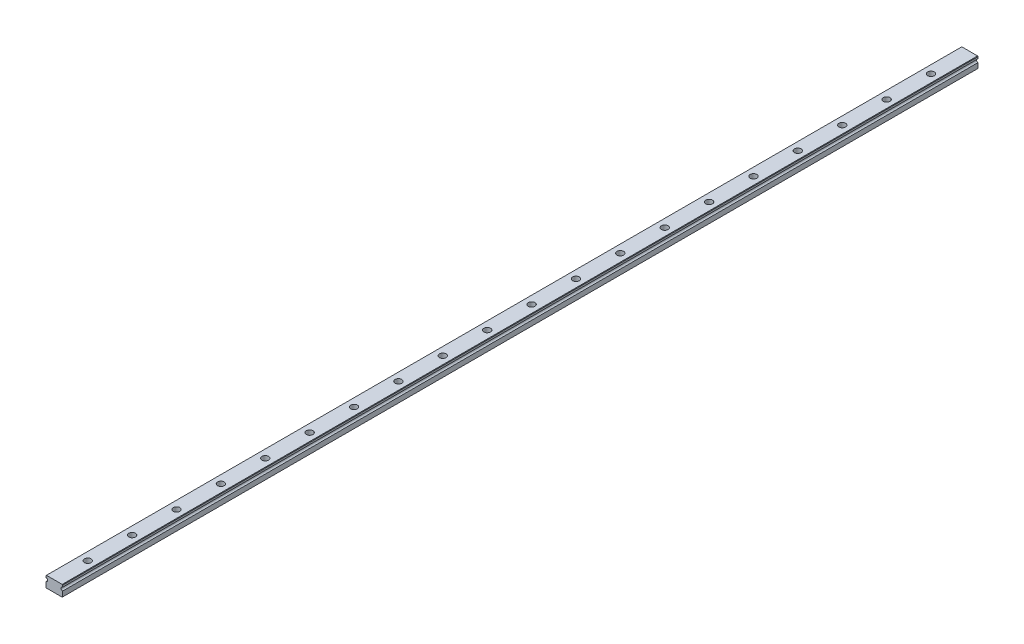
SolidWorks part; units mm, degrees
material "镀铬不锈钢"
ref_plane "前视基准面" through (0, 0, 0) normal (0, 0, 1) x (1, 0, 0)
ref_plane "上视基准面" through (0, 0, 0) normal (0, 1, 0) x (1, 0, 0)
ref_plane "右视基准面" through (0, 0, 0) normal (1, 0, 0) x (0, 0, -1)
other "Configuration Table"
sketch "草图1" plane through (0, 0, 0) normal (0, 0, 1) x (1, 0, 0)
  line L0 (-7.6432, 0.2342) -> (-7.6432, -4.3658)
  line L1 (-7.6432, -4.3658) -> (-7.2432, -4.7658)
  line L2 (-7.2432, -4.7658) -> (6.9568, -4.7658)
  line L3 (6.9568, -4.7658) -> (7.3568, -4.3658)
  line L4 (7.3568, -4.3658) -> (7.3568, 0.2342)
  line L5 (7.3568, 3.2342) -> (7.3568, 4.8342)
  line L6 (7.3568, 4.8342) -> (6.9568, 5.2342)
  line L7 (6.9568, 5.2342) -> (-7.2432, 5.2342)
  line L8 (-7.2432, 5.2342) -> (-7.6432, 4.8342)
  line L9 (-7.6432, 4.8342) -> (-7.6432, 3.2342)
  arc A0 (5.8568, 1.7342) -> (7.3568, 0.2342) centre (7.3568, 1.7342) ccw
  arc A1 (7.3568, 3.2342) -> (5.8568, 1.7342) centre (7.3568, 1.7342) ccw
  arc A2 (-7.6432, 0.2342) -> (-7.6432, 3.2342) centre (-7.6432, 1.7342) ccw
extrude "凸台-拉伸1" add sketch "草图1" along normal blind 1000
sketch "草图2" plane through (0, 5.2342, 0) normal (0, 1, 0) x (1, 0, 0)
  line L0 (6.9568, 0) -> (-7.2432, 0) construction
  circle A0 centre (0, -20) radius 1.5
  dimension "D1" = 3
  dimension "D2" = 20
extrude "切除-拉伸1" cut sketch "草图2" against normal blind 20
sketch "草图3" plane through (0, 5.2342, 0) normal (0, 1, 0) x (1, 0, 0)
  circle A0 centre (0, -20) radius 3
  dimension "D1" = 6
extrude "切除-拉伸2" cut sketch "草图3" against normal blind 4.5
sketch "草图4" plane through (0, 5.2342, 0) normal (0, 1, 0) x (1, 0, 0)
  line L0 (0, 0) -> (0, -1341.5051) construction
pattern_linear "阵列(线性)1" count 25 spacing 40 along (0, 0, 1) of "切除-拉伸2", "切除-拉伸1"
sketch "草图5" plane through (0, 0, 1000) normal (0, 0, 1) x (1, 0, 0)
  line L10 (-7.6432, 0.2342) -> (-7.6432, -4.3658)
  line L11 (-7.6432, -4.3658) -> (-7.2432, -4.7658)
  line L12 (-7.2432, -4.7658) -> (6.9568, -4.7658)
  line L13 (6.9568, -4.7658) -> (7.3568, -4.3658)
  line L14 (7.3568, -4.3658) -> (7.3568, 0.2342)
  line L15 (7.3568, 3.2342) -> (7.3568, 4.8342)
  line L16 (7.3568, 4.8342) -> (6.9568, 5.2342)
  line L17 (6.9568, 5.2342) -> (-7.2432, 5.2342)
  line L18 (-7.2432, 5.2342) -> (-7.6432, 4.8342)
  line L19 (-7.6432, 4.8342) -> (-7.6432, 3.2342)
  line L20 (-7.6432, 0.2342) -> (-7.6432, -4.3658)
  line L21 (-7.6432, -4.3658) -> (-7.2432, -4.7658)
  line L22 (-7.2432, -4.7658) -> (6.9568, -4.7658)
  line L23 (6.9568, -4.7658) -> (7.3568, -4.3658)
  line L24 (7.3568, -4.3658) -> (7.3568, 0.2342)
  line L25 (7.3568, 3.2342) -> (7.3568, 4.8342)
  line L26 (7.3568, 4.8342) -> (6.9568, 5.2342)
  line L27 (6.9568, 5.2342) -> (-7.2432, 5.2342)
  line L28 (-7.2432, 5.2342) -> (-7.6432, 4.8342)
  line L29 (-7.6432, 4.8342) -> (-7.6432, 3.2342)
  arc A2 (-7.6432, 0.2342) -> (-7.6432, 3.2342) centre (-7.6432, 1.7342) ccw
  arc A3 (7.3568, 3.2342) -> (7.3568, 0.2342) centre (7.3568, 1.7342) ccw
  arc A4 (-7.6432, 0.2342) -> (-7.6432, 3.2342) centre (-7.6432, 1.7342) ccw
  arc A5 (7.3568, 3.2342) -> (7.3568, 0.2342) centre (7.3568, 1.7342) ccw
  dimension "D1" = 0
sketch "草图6" plane through (0, 0, 0) normal (0, 0, -1) x (-1, 0, 0)
  line L10 (7.6432, 3.2342) -> (7.6432, 4.8342)
  line L11 (7.6432, 4.8342) -> (7.2432, 5.2342)
  line L12 (7.2432, 5.2342) -> (-6.9568, 5.2342)
  line L13 (-6.9568, 5.2342) -> (-7.3568, 4.8342)
  line L14 (-7.3568, 4.8342) -> (-7.3568, 3.2342)
  line L15 (-7.3568, 0.2342) -> (-7.3568, -4.3658)
  line L16 (-7.3568, -4.3658) -> (-6.9568, -4.7658)
  line L17 (-6.9568, -4.7658) -> (7.2432, -4.7658)
  line L18 (7.2432, -4.7658) -> (7.6432, -4.3658)
  line L19 (7.6432, -4.3658) -> (7.6432, 0.2342)
  line L20 (7.6432, 3.2342) -> (7.6432, 4.8342)
  line L21 (7.6432, 4.8342) -> (7.2432, 5.2342)
  line L22 (7.2432, 5.2342) -> (-6.9568, 5.2342)
  line L23 (-6.9568, 5.2342) -> (-7.3568, 4.8342)
  line L24 (-7.3568, 4.8342) -> (-7.3568, 3.2342)
  line L25 (-7.3568, 0.2342) -> (-7.3568, -4.3658)
  line L26 (-7.3568, -4.3658) -> (-6.9568, -4.7658)
  line L27 (-6.9568, -4.7658) -> (7.2432, -4.7658)
  line L28 (7.2432, -4.7658) -> (7.6432, -4.3658)
  line L29 (7.6432, -4.3658) -> (7.6432, 0.2342)
  arc A2 (7.6432, 3.2342) -> (7.6432, 0.2342) centre (7.6432, 1.7342) ccw
  arc A3 (-7.3568, 0.2342) -> (-7.3568, 3.2342) centre (-7.3568, 1.7342) ccw
  arc A4 (7.6432, 3.2342) -> (7.6432, 0.2342) centre (7.6432, 1.7342) ccw
  arc A5 (-7.3568, 0.2342) -> (-7.3568, 3.2342) centre (-7.3568, 1.7342) ccw
  dimension "D1" = 0
extrude "切除-拉伸4" cut sketch "草图6" against normal blind 80
sketch "草图7" plane through (0, 0, 80) normal (0, 0, -1) x (-1, 0, 0)
  line L10 (7.6432, 3.2342) -> (7.6432, 4.8342)
  line L11 (7.6432, 4.8342) -> (7.2432, 5.2342)
  line L12 (7.2432, 5.2342) -> (-6.9568, 5.2342)
  line L13 (-6.9568, 5.2342) -> (-7.3568, 4.8342)
  line L14 (-7.3568, 4.8342) -> (-7.3568, 3.2342)
  line L15 (-7.3568, 0.2342) -> (-7.3568, -4.3658)
  line L16 (-7.3568, -4.3658) -> (-6.9568, -4.7658)
  line L17 (-6.9568, -4.7658) -> (7.2432, -4.7658)
  line L18 (7.2432, -4.7658) -> (7.6432, -4.3658)
  line L19 (7.6432, -4.3658) -> (7.6432, 0.2342)
  line L20 (7.6432, 3.2342) -> (7.6432, 4.8342)
  line L21 (7.6432, 4.8342) -> (7.2432, 5.2342)
  line L22 (7.2432, 5.2342) -> (-6.9568, 5.2342)
  line L23 (-6.9568, 5.2342) -> (-7.3568, 4.8342)
  line L24 (-7.3568, 4.8342) -> (-7.3568, 3.2342)
  line L25 (-7.3568, 0.2342) -> (-7.3568, -4.3658)
  line L26 (-7.3568, -4.3658) -> (-6.9568, -4.7658)
  line L27 (-6.9568, -4.7658) -> (7.2432, -4.7658)
  line L28 (7.2432, -4.7658) -> (7.6432, -4.3658)
  line L29 (7.6432, -4.3658) -> (7.6432, 0.2342)
  arc A2 (7.6432, 3.2342) -> (7.6432, 0.2342) centre (7.6432, 1.7342) ccw
  arc A3 (-7.3568, 0.2342) -> (-7.3568, 3.2342) centre (-7.3568, 1.7342) ccw
  arc A4 (7.6432, 3.2342) -> (7.6432, 0.2342) centre (7.6432, 1.7342) ccw
  arc A5 (-7.3568, 0.2342) -> (-7.3568, 3.2342) centre (-7.3568, 1.7342) ccw
  dimension "D1" = 0
extrude "切除-拉伸5" cut sketch "草图7" against normal blind 80
sketch "草图8" plane through (0, 0, 160) normal (0, 0, -1) x (-1, 0, 0)
  line L10 (7.6432, 3.2342) -> (7.6432, 4.8342)
  line L11 (7.6432, 4.8342) -> (7.2432, 5.2342)
  line L12 (7.2432, 5.2342) -> (-6.9568, 5.2342)
  line L13 (-6.9568, 5.2342) -> (-7.3568, 4.8342)
  line L14 (-7.3568, 4.8342) -> (-7.3568, 3.2342)
  line L15 (-7.3568, 0.2342) -> (-7.3568, -4.3658)
  line L16 (-7.3568, -4.3658) -> (-6.9568, -4.7658)
  line L17 (-6.9568, -4.7658) -> (7.2432, -4.7658)
  line L18 (7.2432, -4.7658) -> (7.6432, -4.3658)
  line L19 (7.6432, -4.3658) -> (7.6432, 0.2342)
  line L20 (7.6432, 3.2342) -> (7.6432, 4.8342)
  line L21 (7.6432, 4.8342) -> (7.2432, 5.2342)
  line L22 (7.2432, 5.2342) -> (-6.9568, 5.2342)
  line L23 (-6.9568, 5.2342) -> (-7.3568, 4.8342)
  line L24 (-7.3568, 4.8342) -> (-7.3568, 3.2342)
  line L25 (-7.3568, 0.2342) -> (-7.3568, -4.3658)
  line L26 (-7.3568, -4.3658) -> (-6.9568, -4.7658)
  line L27 (-6.9568, -4.7658) -> (7.2432, -4.7658)
  line L28 (7.2432, -4.7658) -> (7.6432, -4.3658)
  line L29 (7.6432, -4.3658) -> (7.6432, 0.2342)
  arc A2 (7.6432, 3.2342) -> (7.6432, 0.2342) centre (7.6432, 1.7342) ccw
  arc A3 (-7.3568, 0.2342) -> (-7.3568, 3.2342) centre (-7.3568, 1.7342) ccw
  arc A4 (7.6432, 3.2342) -> (7.6432, 0.2342) centre (7.6432, 1.7342) ccw
  arc A5 (-7.3568, 0.2342) -> (-7.3568, 3.2342) centre (-7.3568, 1.7342) ccw
  dimension "D1" = 0
extrude "切除-拉伸6" [suppressed] cut sketch "草图8" against normal blind 20
sketch "草图9" plane through (0, 0, 1000) normal (0, 0, 1) x (1, 0, 0)
  line L10 (-7.6432, 0.2342) -> (-7.6432, -4.3658)
  line L11 (-7.6432, -4.3658) -> (-7.2432, -4.7658)
  line L12 (-7.2432, -4.7658) -> (6.9568, -4.7658)
  line L13 (6.9568, -4.7658) -> (7.3568, -4.3658)
  line L14 (7.3568, -4.3658) -> (7.3568, 0.2342)
  line L15 (7.3568, 3.2342) -> (7.3568, 4.8342)
  line L16 (7.3568, 4.8342) -> (6.9568, 5.2342)
  line L17 (6.9568, 5.2342) -> (-7.2432, 5.2342)
  line L18 (-7.2432, 5.2342) -> (-7.6432, 4.8342)
  line L19 (-7.6432, 4.8342) -> (-7.6432, 3.2342)
  line L20 (-7.6432, 0.2342) -> (-7.6432, -4.3658)
  line L21 (-7.6432, -4.3658) -> (-7.2432, -4.7658)
  line L22 (-7.2432, -4.7658) -> (6.9568, -4.7658)
  line L23 (6.9568, -4.7658) -> (7.3568, -4.3658)
  line L24 (7.3568, -4.3658) -> (7.3568, 0.2342)
  line L25 (7.3568, 3.2342) -> (7.3568, 4.8342)
  line L26 (7.3568, 4.8342) -> (6.9568, 5.2342)
  line L27 (6.9568, 5.2342) -> (-7.2432, 5.2342)
  line L28 (-7.2432, 5.2342) -> (-7.6432, 4.8342)
  line L29 (-7.6432, 4.8342) -> (-7.6432, 3.2342)
  arc A2 (-7.6432, 0.2342) -> (-7.6432, 3.2342) centre (-7.6432, 1.7342) ccw
  arc A3 (7.3568, 3.2342) -> (7.3568, 0.2342) centre (7.3568, 1.7342) ccw
  arc A4 (-7.6432, 0.2342) -> (-7.6432, 3.2342) centre (-7.6432, 1.7342) ccw
  arc A5 (7.3568, 3.2342) -> (7.3568, 0.2342) centre (7.3568, 1.7342) ccw
  dimension "D1" = 0
extrude "切除-拉伸7" [suppressed] cut sketch "草图9" against normal blind 360
sketch "草图10" plane through (0, 0, 160) normal (0, 0, -1) x (-1, 0, 0)
  line L10 (7.6432, 3.2342) -> (7.6432, 4.8342)
  line L11 (7.6432, 4.8342) -> (7.2432, 5.2342)
  line L12 (7.2432, 5.2342) -> (-6.9568, 5.2342)
  line L13 (-6.9568, 5.2342) -> (-7.3568, 4.8342)
  line L14 (-7.3568, 4.8342) -> (-7.3568, 3.2342)
  line L15 (-7.3568, 0.2342) -> (-7.3568, -4.3658)
  line L16 (-7.3568, -4.3658) -> (-6.9568, -4.7658)
  line L17 (-6.9568, -4.7658) -> (7.2432, -4.7658)
  line L18 (7.2432, -4.7658) -> (7.6432, -4.3658)
  line L19 (7.6432, -4.3658) -> (7.6432, 0.2342)
  line L20 (7.6432, 3.2342) -> (7.6432, 4.8342)
  line L21 (7.6432, 4.8342) -> (7.2432, 5.2342)
  line L22 (7.2432, 5.2342) -> (-6.9568, 5.2342)
  line L23 (-6.9568, 5.2342) -> (-7.3568, 4.8342)
  line L24 (-7.3568, 4.8342) -> (-7.3568, 3.2342)
  line L25 (-7.3568, 0.2342) -> (-7.3568, -4.3658)
  line L26 (-7.3568, -4.3658) -> (-6.9568, -4.7658)
  line L27 (-6.9568, -4.7658) -> (7.2432, -4.7658)
  line L28 (7.2432, -4.7658) -> (7.6432, -4.3658)
  line L29 (7.6432, -4.3658) -> (7.6432, 0.2342)
  arc A2 (7.6432, 3.2342) -> (7.6432, 0.2342) centre (7.6432, 1.7342) ccw
  arc A3 (-7.3568, 0.2342) -> (-7.3568, 3.2342) centre (-7.3568, 1.7342) ccw
  arc A4 (7.6432, 3.2342) -> (7.6432, 0.2342) centre (7.6432, 1.7342) ccw
  arc A5 (-7.3568, 0.2342) -> (-7.3568, 3.2342) centre (-7.3568, 1.7342) ccw
  dimension "D1" = 0
extrude "凸台-拉伸2" add sketch "草图10" along normal blind 15
sketch "草图11" plane through (0, 0, 1000) normal (0, 0, 1) x (1, 0, 0)
  line L10 (-7.6432, 0.2342) -> (-7.6432, -4.3658)
  line L11 (-7.6432, -4.3658) -> (-7.2432, -4.7658)
  line L12 (-7.2432, -4.7658) -> (6.9568, -4.7658)
  line L13 (6.9568, -4.7658) -> (7.3568, -4.3658)
  line L14 (7.3568, -4.3658) -> (7.3568, 0.2342)
  line L15 (7.3568, 3.2342) -> (7.3568, 4.8342)
  line L16 (7.3568, 4.8342) -> (6.9568, 5.2342)
  line L17 (6.9568, 5.2342) -> (-7.2432, 5.2342)
  line L18 (-7.2432, 5.2342) -> (-7.6432, 4.8342)
  line L19 (-7.6432, 4.8342) -> (-7.6432, 3.2342)
  line L20 (-7.6432, 0.2342) -> (-7.6432, -4.3658)
  line L21 (-7.6432, -4.3658) -> (-7.2432, -4.7658)
  line L22 (-7.2432, -4.7658) -> (6.9568, -4.7658)
  line L23 (6.9568, -4.7658) -> (7.3568, -4.3658)
  line L24 (7.3568, -4.3658) -> (7.3568, 0.2342)
  line L25 (7.3568, 3.2342) -> (7.3568, 4.8342)
  line L26 (7.3568, 4.8342) -> (6.9568, 5.2342)
  line L27 (6.9568, 5.2342) -> (-7.2432, 5.2342)
  line L28 (-7.2432, 5.2342) -> (-7.6432, 4.8342)
  line L29 (-7.6432, 4.8342) -> (-7.6432, 3.2342)
  arc A2 (-7.6432, 0.2342) -> (-7.6432, 3.2342) centre (-7.6432, 1.7342) ccw
  arc A3 (7.3568, 3.2342) -> (7.3568, 0.2342) centre (7.3568, 1.7342) ccw
  arc A4 (-7.6432, 0.2342) -> (-7.6432, 3.2342) centre (-7.6432, 1.7342) ccw
  arc A5 (7.3568, 3.2342) -> (7.3568, 0.2342) centre (7.3568, 1.7342) ccw
  dimension "D1" = 0
extrude "切除-拉伸8" cut sketch "草图11" against normal blind 30
